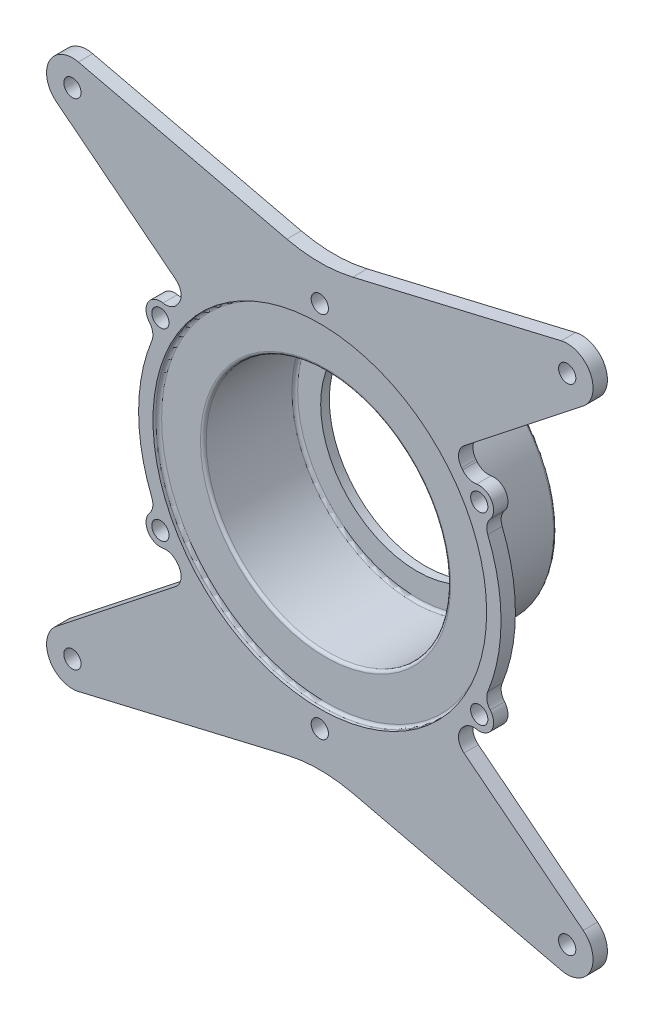
SolidWorks part; units mm, degrees
material "7075-O (SS)"
ref_plane "Front Plane" through (0, 0, 0) normal (0, 0, 1) x (1, 0, 0)
ref_plane "Top Plane" through (0, 0, 0) normal (0, 1, 0) x (1, 0, 0)
ref_plane "Right Plane" through (0, 0, 0) normal (1, 0, 0) x (0, 0, -1)
sketch "Sketch2" plane through (0, 0, 0) normal (1, 0, 0) x (0, 0, -1)
  line L0 (-59.9535, 0) -> (59.9535, 0) construction
  line L1 (10.3257, 42.5) -> (42.1257, 42.5)
  line L2 (8.3257, 63) -> (8.3257, 58)
  line L3 (42.1257, 42.5) -> (42.1257, 33.5)
  line L4 (13.3257, 63) -> (13.3257, 45.5)
  line L5 (13.3257, 45.5) -> (45.1257, 45.5)
  line L6 (45.1257, 45.5) -> (45.1257, 33.5)
  line L7 (8.3257, 63) -> (13.3257, 63)
  line L8 (42.1257, 33.5) -> (45.1257, 33.5)
  line L9 (8.3257, 58) -> (10.3257, 58)
  line L10 (10.3257, 58) -> (10.3257, 42.5)
  point P4 (0, 0)
  dimension "D1" = 42.5
  dimension "D2" = 33.5
  dimension "D3" = 31.8
  dimension "D4" = 63
  dimension "D6" = 5
  dimension "D5" = 3
  dimension "D7" = 3
  dimension "D8" = 5
  dimension "D9" = 2
revolve "Revolve1" add sketch "Sketch2" angle 360 about L0
sketch "Sketch3" plane through (0, 0, -8.3257) normal (0, 0, 1) x (1, 0, 0)
  line L4 (0, 59) -> (0, 64) construction
  line L27 (11.4619, -77.6918) -> (83.9369, -94.7603)
  line L28 (91.5721, -78.9324) -> (42.8702, -40.5358)
  line L29 (42.8702, 40.5358) -> (91.5721, 78.9324)
  line L30 (83.9369, 94.7603) -> (11.4619, 77.6918)
  line L31 (-11.4619, 77.6918) -> (-83.9369, 94.7603)
  line L32 (-91.5721, 78.9324) -> (-42.8702, 40.5358)
  line L33 (-42.8702, -40.5358) -> (-91.5721, -78.9324)
  line L34 (-83.9369, -94.7603) -> (-11.4619, -77.6918)
  line L35 (0, 64) -> (0, 0) construction
  circle A18 centre (55.4256, 32) radius 5
  circle A55 centre (55.4256, 32) radius 3
  circle A56 centre (55.4256, -32) radius 5
  circle A57 centre (55.4256, -32) radius 3
  circle A58 centre (0, -64) radius 5
  circle A67 centre (0, -64) radius 3
  circle A68 centre (-55.4256, -32) radius 5
  circle A69 centre (-55.4256, -32) radius 3
  circle A70 centre (-55.4256, 32) radius 5
  circle A71 centre (0, 64) radius 5
  circle A77 centre (0, 64) radius 3
  circle A83 centre (-55.4256, 32) radius 3
  arc A115 (-89, -86) -> (-83, -86) centre (-86, -86) ccw
  arc A116 (-83, -86) -> (-89, -86) centre (-86, -86) ccw
  arc A117 (83, -86) -> (89, -86) centre (86, -86) ccw
  arc A118 (89, -86) -> (83, -86) centre (86, -86) ccw
  arc A119 (89, 86) -> (83, 86) centre (86, 86) ccw
  arc A120 (83, 86) -> (89, 86) centre (86, 86) ccw
  arc A121 (-83, 86) -> (-89, 86) centre (-86, 86) ccw
  arc A122 (-89, 86) -> (-83, 86) centre (-86, 86) ccw
  arc A123 (83.9369, -94.7603) -> (95, -86) centre (86, -86) ccw
  arc A124 (95, -86) -> (91.5721, -78.9324) centre (86, -86) ccw
  arc A130 (91.5721, 78.9324) -> (95, 86) centre (86, 86) ccw
  arc A131 (95, 86) -> (83.9369, 94.7603) centre (86, 86) ccw
  arc A132 (-11.4619, 77.6918) -> (11.4619, 77.6918) centre (0, 126.3603) ccw
  arc A133 (-83.9369, 94.7603) -> (-91.5721, 78.9324) centre (-86, 86) ccw
  arc A142 (-91.5721, -78.9324) -> (-83.9369, -94.7603) centre (-86, -86) ccw
  arc A143 (11.4619, -77.6918) -> (-11.4619, -77.6918) centre (0, -126.3603) ccw
  arc A144 (42.8702, 40.5358) -> (-42.8702, 40.5358) centre (0, 0) ccw
  arc A145 (-42.8702, -40.5358) -> (42.8702, -40.5358) centre (0, 0) ccw
  dimension "D1" = 10
  dimension "D2" = 6
  dimension "D4" = 6
  dimension "D3" = 64
extrude "Boss-Extrude1" add sketch "Sketch3" against normal up to surface (5 mm away)
sketch "Sketch4" plane through (0, 0, -13.3257) normal (0, 0, -1) x (-1, 0, 0)
  circle A0 centre (55.4256, 32) radius 3 construction
  circle A8 centre (55.4256, -32) radius 3 construction
  circle A10 centre (0, -64) radius 3 construction
  circle A22 centre (-55.4256, -32) radius 3 construction
  circle A23 centre (-55.4256, 32) radius 3 construction
  circle A24 centre (0, 64) radius 3 construction
  circle A25 centre (55.4256, 32) radius 3
  circle A26 centre (55.4256, -32) radius 3
  circle A27 centre (0, -64) radius 3
  circle A28 centre (-55.4256, -32) radius 3
  circle A29 centre (-55.4256, 32) radius 3
  circle A30 centre (0, 64) radius 3
extrude "Cut-Extrude1" cut sketch "Sketch4" against normal up to surface (5 mm away)
fillet "Fillet1" radius 1 5 edges at (42.5, 0, -42.1257) (45.5, 0, -45.1257) (45.5, 0, -13.3257) (58, 0, -10.3257) (42.5, 0, -10.3257)
fillet "Fillet2" radius 5 4 edges at (-46.0232, -43.0217, -10.8257) (-46.0232, 43.0217, -10.8257) (46.0232, -43.0217, -10.8257) (46.0232, 43.0217, -10.8257)
fillet "Fillet3" radius 5 8 edges at (-51.9688, -35.6125, -10.8257) (-56.8257, -27.2, -10.8257) (-56.8257, 27.2, -10.8257) (-51.9688, 35.6125, -10.8257) (56.8257, -27.2, -10.8257) (51.9688, -35.6125, -10.8257) (51.9688, 35.6125, -10.8257) (56.8257, 27.2, -10.8257)
